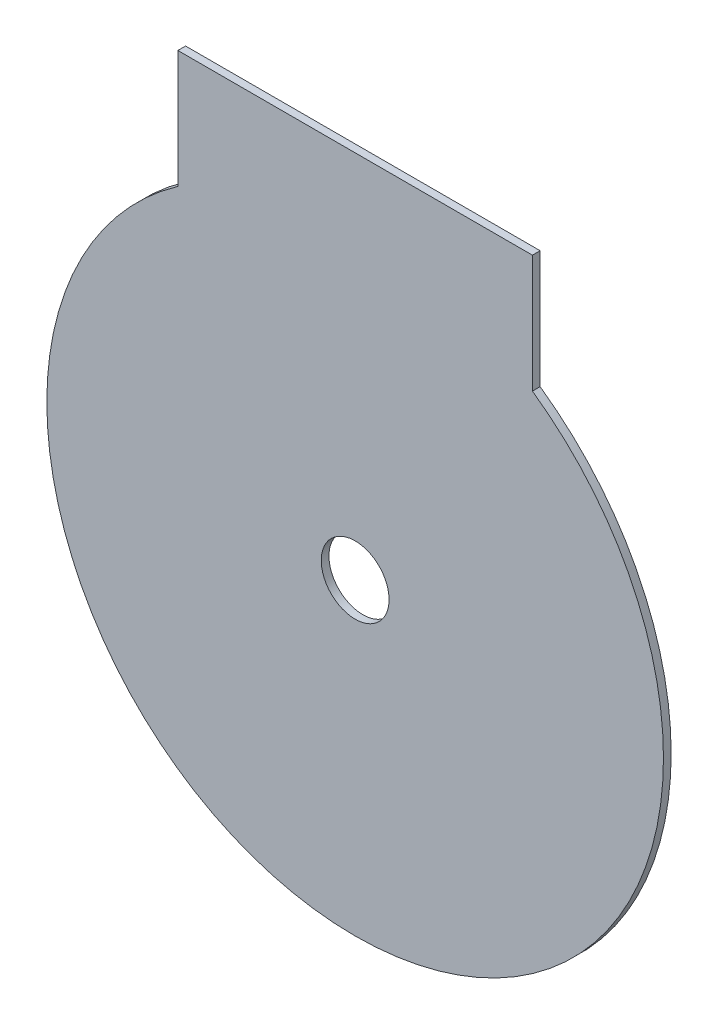
SolidWorks part; units mm, degrees
material "ABS PC"
ref_plane "Front Plane" through (0, 0, 0) normal (0, 0, 1) x (1, 0, 0)
ref_plane "Top Plane" through (0, 0, 0) normal (0, 1, 0) x (1, 0, 0)
ref_plane "Right Plane" through (0, 0, 0) normal (1, 0, 0) x (0, 0, -1)
sketch "Sketch2" plane through (0, 0, 0) normal (0, 0, 1) x (1, 0, 0)
  line L0 (-57.5, 249) -> (-57.5, 210.8153)
  line L5 (-150.8125, 249) -> (150.8125, 249) construction
  line L6 (-150.8125, 254) -> (150.8125, 254) construction
  line L7 (0, 254) -> (0, 0) construction
  line L9 (57.5, 249) -> (57.5, 210.8153)
  line L10 (57.5, 249) -> (-57.5, 249)
  arc A0 (-57.5, 210.8153) -> (57.5, 210.8153) centre (0, 129) ccw
  circle A1 centre (0, 129) radius 11
  dimension "D2" = 22
  dimension "D3" = 100
  dimension "D1" = 120
  dimension "D4" = 115
extrude "Boss-Extrude1" add sketch "Sketch2" along normal blind 2.5
